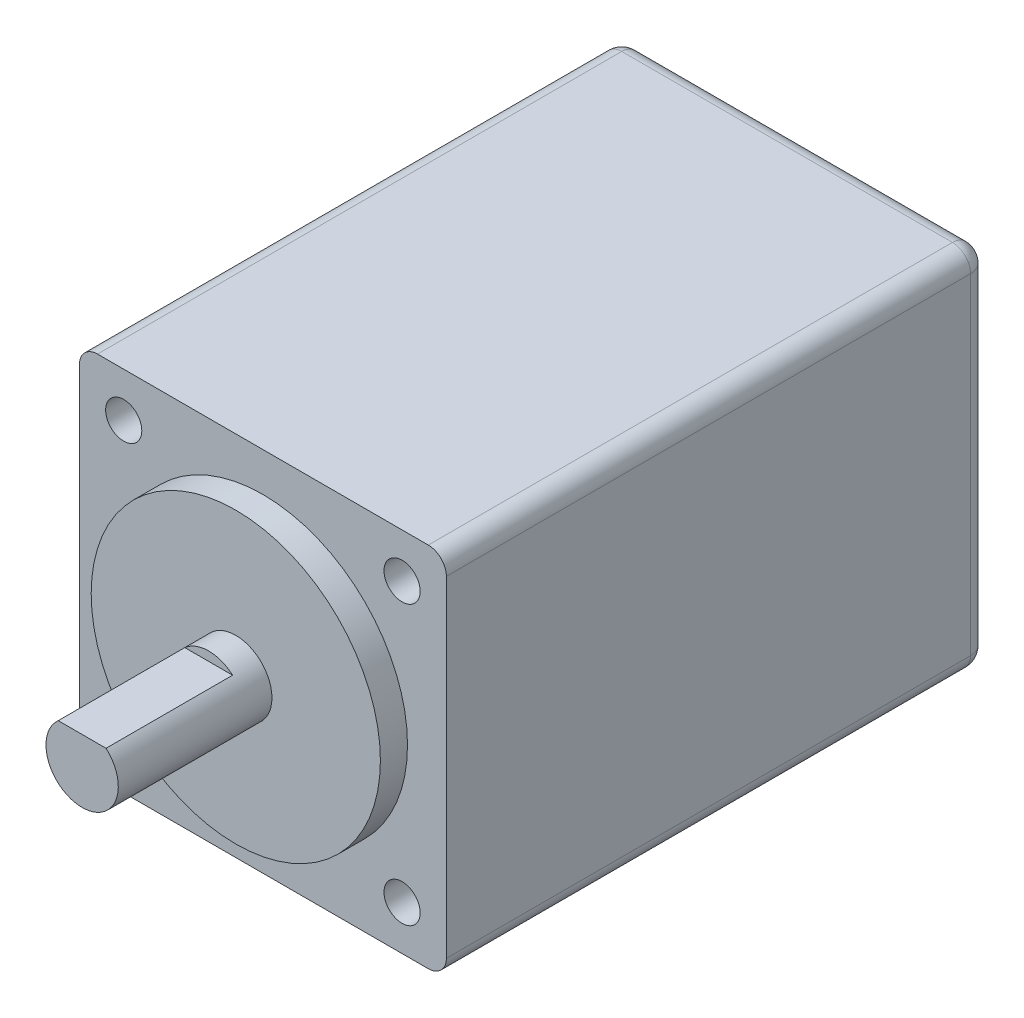
SolidWorks part; units mm, degrees
ref_plane "Front Plane" through (0, 0, 0) normal (0, 0, 1) x (1, 0, 0)
ref_plane "Top Plane" through (0, 0, 0) normal (0, 1, 0) x (1, 0, 0)
ref_plane "Right Plane" through (0, 0, 0) normal (1, 0, 0) x (0, 0, -1)
sketch "Sketch1" plane through (0, 0, 0) normal (0, 0, 1) x (1, 0, 0)
  line L1 (-10.15, -10.15) -> (10.15, -10.15)
  line L2 (-10.15, -10.15) -> (-10.15, 10.15)
  line L3 (-10.15, 10.15) -> (10.15, 10.15)
  line L4 (10.15, -10.15) -> (10.15, 10.15)
  line L5 (-10.15, -10.15) -> (10.15, 10.15) construction
  line L6 (-10.15, 10.15) -> (10.15, -10.15) construction
  point P0 (0, 0)
  dimension "D1" = 20.3
  dimension "D2" = 20.3
extrude "Boss-Extrude1" add sketch "Sketch1" along normal blind 30
sketch "Sketch2" plane through (0, 0, 30) normal (0, 0, 1) x (1, 0, 0)
  circle A0 centre (0, 0) radius 8
  dimension "D1" = 16
extrude "Boss-Extrude2" add sketch "Sketch2" along normal blind 1.5
sketch "Sketch3" plane through (0, 0, 31.5) normal (0, 0, 1) x (1, 0, 0)
  circle A0 centre (0, 0) radius 2
  dimension "D1" = 4
extrude "Boss-Extrude3" add sketch "Sketch3" along normal blind 8.5
sketch "Sketch4" plane through (0, 0, 0) normal (1, 0, 0) x (0, 0, -1)
  line L1 (-40, 2) -> (-33, 2)
  line L2 (-40, 2) -> (-40, 1.5)
  line L3 (-40, 1.5) -> (-33, 1.5)
  line L4 (-33, 2) -> (-33, 1.5)
  dimension "D1" = 7
  dimension "D2" = 0.5
extrude "Cut-Extrude1" cut sketch "Sketch4" against normal mid plane 10
sketch "Sketch5" plane through (0, 0, 30) normal (0, 0, 1) x (1, 0, 0)
  line L1 (-7.7, -7.7) -> (7.7, -7.7) construction
  line L2 (-7.7, -7.7) -> (-7.7, 7.7) construction
  line L3 (-7.7, 7.7) -> (7.7, 7.7) construction
  line L4 (7.7, -7.7) -> (7.7, 7.7) construction
  line L5 (-7.7, -7.7) -> (7.7, 7.7) construction
  line L6 (-7.7, 7.7) -> (7.7, -7.7) construction
  circle A0 centre (-7.7, 7.7) radius 1
  circle A1 centre (7.7, 7.7) radius 1
  circle A2 centre (7.7, -7.7) radius 1
  circle A3 centre (-7.7, -7.7) radius 1
  point P0 (0, 0)
  dimension "D3" = 2
  dimension "D1" = 15.4
  dimension "D2" = 15.4
  dimension "D4" = 4
extrude "Cut-Extrude2" cut sketch "Sketch5" against normal blind 2.5
fillet "Fillet1" radius 1 8 edges at (0, 10.15, 0) (-10.15, 0, 0) (0, -10.15, 0) (10.15, 0, 0) (-10.15, -10.15, 15) (10.15, -10.15, 15) (-10.15, 10.15, 15) (10.15, 10.15, 15)
